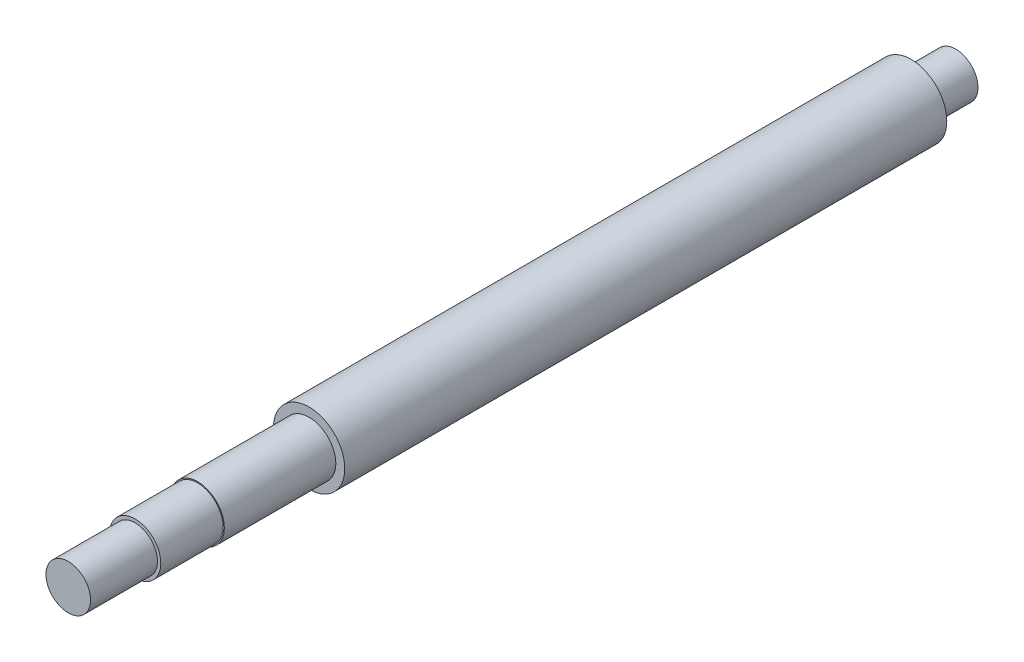
SolidWorks part; units mm, degrees
ref_plane "정면" through (0, 0, 0) normal (0, 0, 1) x (1, 0, 0)
ref_plane "윗면" through (0, 0, 0) normal (0, 1, 0) x (1, 0, 0)
ref_plane "우측면" through (0, 0, 0) normal (1, 0, 0) x (0, 0, -1)
sketch "스케치1" plane through (0, 0, 0) normal (0, 0, 1) x (1, 0, 0)
  circle A0 centre (0, 0) radius 5
  dimension "D1" = 10
extrude "보스-돌출1" add sketch "스케치1" along normal blind 10
sketch "스케치2" plane through (0, 0, 10) normal (0, 0, 1) x (1, 0, 0)
  circle A0 centre (0, 0) radius 8
  dimension "D1" = 16
extrude "보스-돌출2" add sketch "스케치2" along normal blind 135
sketch "스케치3" plane through (0, 0, 145) normal (0, 0, 1) x (1, 0, 0)
  circle A0 centre (0, 0) radius 6
  dimension "D1" = 12
extrude "보스-돌출3" add sketch "스케치3" along normal blind 25
sketch "스케치4" plane through (0, 0, 170) normal (0, 0, 1) x (1, 0, 0)
  circle A0 centre (0, 0) radius 5.75
  dimension "D1" = 11.5
extrude "보스-돌출4" add sketch "스케치4" along normal blind 14
sketch "스케치5" plane through (0, 0, 184) normal (0, 0, 1) x (1, 0, 0)
  circle A0 centre (0, 0) radius 5
extrude "보스-돌출5" add sketch "스케치5" along normal blind 15
